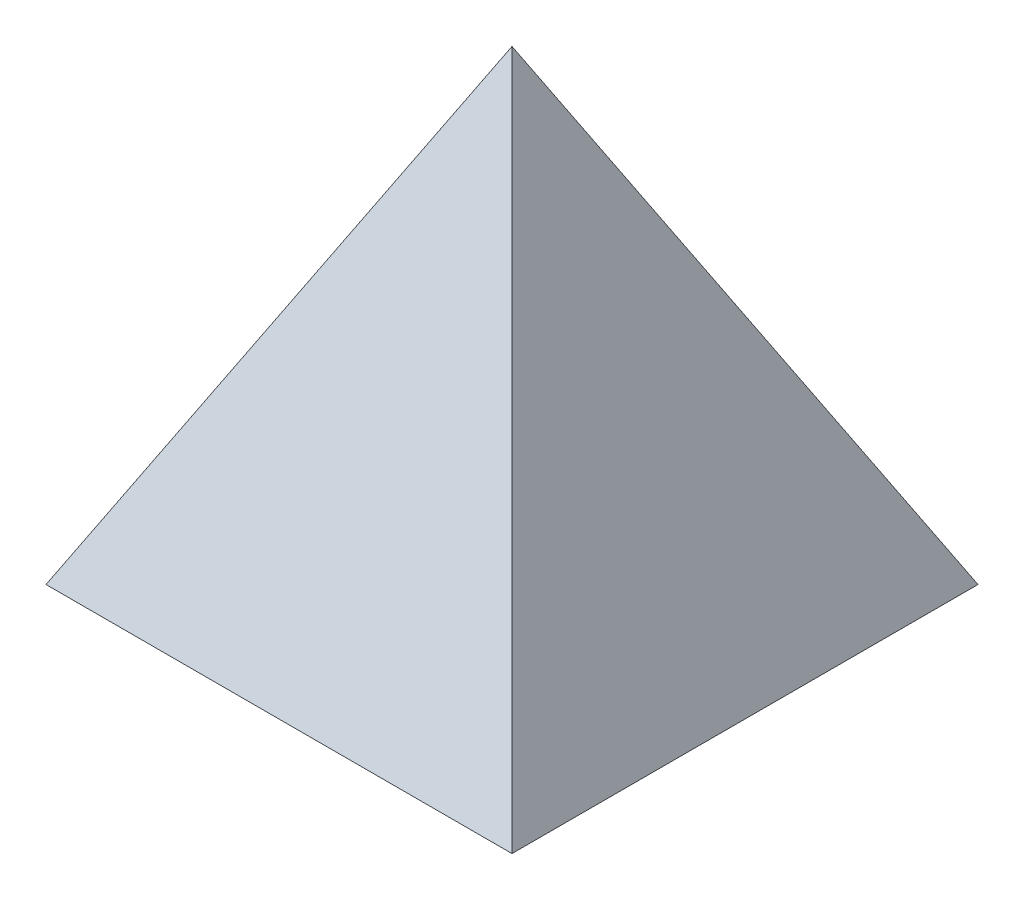
SolidWorks part; units mm, degrees
ref_plane "Front Plane" through (0, 0, 0) normal (0, 0, 1) x (1, 0, 0)
ref_plane "Top Plane" through (0, 0, 0) normal (0, 1, 0) x (1, 0, 0)
ref_plane "Right Plane" through (0, 0, 0) normal (1, 0, 0) x (0, 0, -1)
sketch "Sketch1" plane through (0, 0, 0) normal (0, 1, 0) x (1, 0, 0)
  line L1 (0, 0) -> (50, 0)
  line L2 (0, 0) -> (0, 50)
  line L3 (0, 50) -> (50, 50)
  line L4 (50, 0) -> (50, 50)
extrude "Boss-Extrude1" add sketch "Sketch1" along normal blind 50
sketch "Sketch2" plane through (0, 0, 0) normal (0, 0, 1) x (1, 0, 0)
  line L0 (0, 0) -> (25, 50)
  line L1 (0, 50) -> (50, 50) construction
  line L2 (25, 50) -> (0, 50)
  line L3 (0, 50) -> (0, 0)
extrude "Cut-Extrude1" cut sketch "Sketch2" against normal blind 50
sketch "Sketch3" plane through (0, 0, 0) normal (0, 0, 1) x (1, 0, 0)
  line L0 (25, 50) -> (50, 0)
  line L1 (50, 0) -> (50, 50)
  line L2 (50, 50) -> (25, 50)
extrude "Cut-Extrude2" cut sketch "Sketch3" against normal blind 50
sketch "Sketch4" plane through (0, 0, 0) normal (1, 0, 0) x (0, 0, -1)
  line L0 (0, 0) -> (25, 50)
  line L1 (50, 50) -> (0, 50) construction
  line L2 (25, 50) -> (0, 50)
  line L3 (0, 50) -> (0, 0)
extrude "Cut-Extrude3" cut sketch "Sketch4" along normal blind 50
sketch "Sketch5" plane through (0, 0, 0) normal (1, 0, 0) x (0, 0, -1)
  line L0 (25, 50) -> (50, 0)
  line L1 (50, 0) -> (50, 50)
  line L2 (50, 50) -> (25, 50)
extrude "Cut-Extrude4" cut sketch "Sketch5" along normal blind 50
